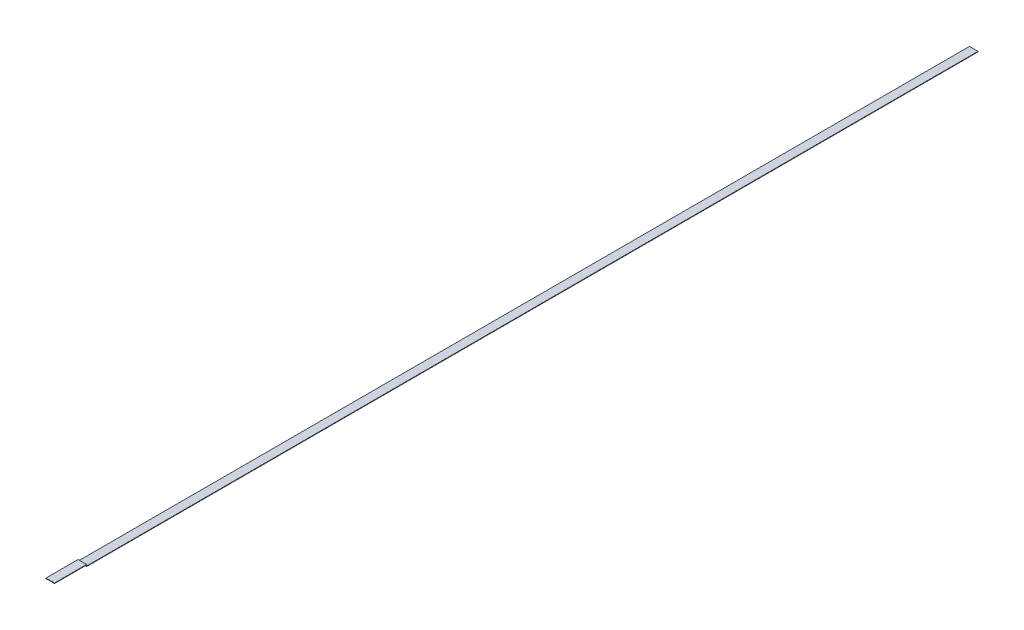
SolidWorks part; units mm, degrees
ref_plane "Front Plane" through (0, 0, 0) normal (0, 0, 1) x (1, 0, 0)
ref_plane "Top Plane" through (0, 0, 0) normal (0, 1, 0) x (1, 0, 0)
ref_plane "Right Plane" through (0, 0, 0) normal (1, 0, 0) x (0, 0, -1)
sketch "Sketch1" plane through (0, 0, 0) normal (0, 1, 0) x (1, 0, 0)
  line L1 (0, 190.5) -> (50.8, 190.5)
  line L2 (0, 190.5) -> (0, 5486.4)
  line L3 (0, 5486.4) -> (50.8, 5486.4)
  line L4 (50.8, 190.5) -> (50.8, 5486.4)
  line L5 (0, 190.5) -> (50.8, 190.5) construction
  line L6 (0, 190.5) -> (0, 0) construction
  line L7 (0, 0) -> (50.8, 0) construction
  line L8 (50.8, 190.5) -> (50.8, 0) construction
  dimension "D1" = 50.8
  dimension "D2" = 5486.4
  dimension "D3" = 190.5
extrude "Boss-Extrude1" add sketch "Sketch1" along normal blind 3.175
ref_plane "Plane1" through (0, 7.9375, 0) normal (0, 1, 0) x (1, 0, 0)
sketch "Sketch2" plane through (0, 7.9375, 0) normal (0, 1, 0) x (1, 0, 0)
  line L1 (0, 0) -> (50.8, 0)
  line L2 (0, 0) -> (0, 190.5)
  line L3 (0, 190.5) -> (50.8, 190.5)
  line L4 (50.8, 0) -> (50.8, 190.5)
extrude "Boss-Extrude2" add sketch "Sketch2" along normal blind 3.175 separate body
